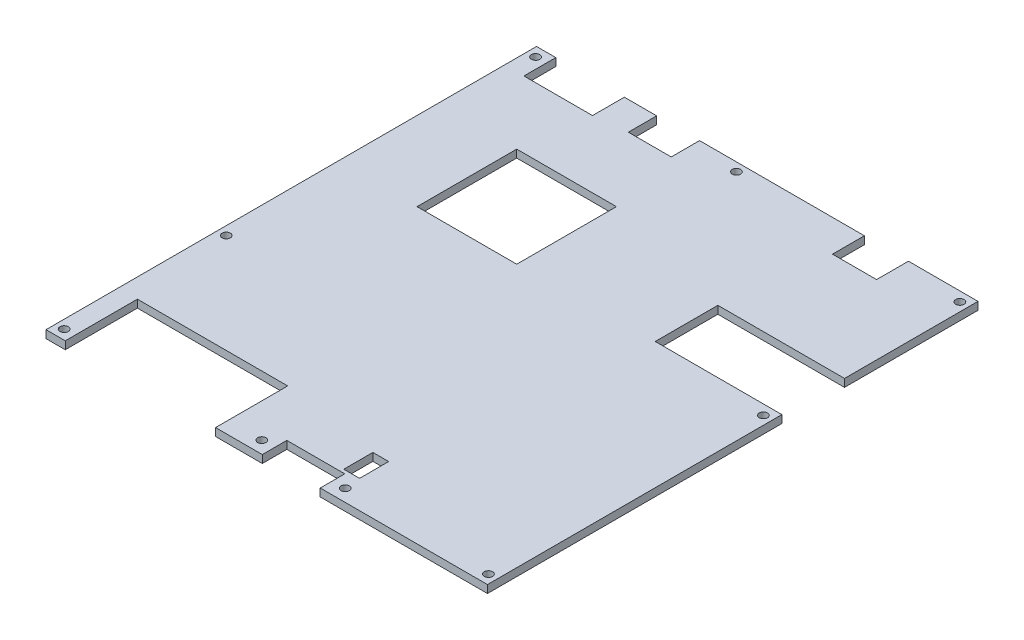
SolidWorks part; units mm, degrees
ref_plane "Front Plane" through (0, 0, 0) normal (0, 0, 1) x (1, 0, 0)
ref_plane "Top Plane" through (0, 0, 0) normal (0, 1, 0) x (1, 0, 0)
ref_plane "Right Plane" through (0, 0, 0) normal (1, 0, 0) x (0, 0, -1)
sketch "Sketch1" plane through (0, 0, 0) normal (0, 1, 0) x (1, 0, 0)
  line L0 (63.5121, 327.7297) -> (677.5121, 327.7297) construction
  line L1 (-90, 100) -> (-82.1461, 100)
  line L2 (-90, 100) -> (-90, -100)
  line L3 (-90, -100) -> (-82.1461, -100)
  line L4 (90, 100) -> (90, 45.5709)
  line L5 (-90, 100) -> (90, -100) construction
  line L6 (-90, -100) -> (90, 100) construction
  line L7 (-6.99, -95) -> (27, -95) construction
  line L8 (-57.7956, 59.7222) -> (-17.1556, 59.7222)
  line L9 (-57.7956, 59.7222) -> (-57.7956, 19.0822)
  line L10 (-57.7956, 19.0822) -> (-17.1556, 19.0822)
  line L11 (-17.1556, 59.7222) -> (-17.1556, 19.0822)
  line L12 (-57.7956, 59.7222) -> (-17.1556, 19.0822) construction
  line L13 (-57.7956, 19.0822) -> (-17.1556, 59.7222) construction
  line L14 (-1.806, -90) -> (21.816, -90)
  line L15 (-1.806, -90) -> (-1.806, -100)
  line L17 (21.816, -90) -> (21.816, -100)
  line L18 (-1.806, -90) -> (21.816, -100) construction
  line L19 (-1.806, -100) -> (21.816, -90) construction
  line L20 (21.816, -100) -> (90, -100)
  line L22 (-82.1461, -100) -> (-82.1461, -70.5895)
  line L23 (-82.1461, -70.5895) -> (-20.8696, -70.5895)
  line L24 (-20.8696, -100) -> (-20.8696, -70.5895)
  line L26 (43.6796, 100) -> (43.6796, 87.0124)
  line L27 (43.6796, 87.0124) -> (61.6362, 87.0124)
  line L28 (61.6362, 100) -> (61.6362, 87.0124)
  line L30 (-41.0187, 100) -> (-41.0187, 88.4478)
  line L31 (-41.0187, 88.4478) -> (-23.5248, 88.4478)
  line L32 (-23.5248, 100) -> (-23.5248, 88.4478)
  line L34 (-82.1461, 100) -> (-82.1461, 87.0124)
  line L35 (-82.1461, 87.0124) -> (-54.1882, 87.0124)
  line L36 (-54.1882, 100) -> (-54.1882, 87.0124)
  line L37 (19.9809, -76.7028) -> (26.4223, -76.7028)
  line L38 (19.9809, -76.7028) -> (19.9809, -88.5675)
  line L39 (19.9809, -88.5675) -> (26.4223, -88.5675)
  line L40 (26.4223, -76.7028) -> (26.4223, -88.5675)
  line L41 (-54.1882, 100) -> (-41.0187, 100)
  line L42 (-23.5248, 100) -> (43.6796, 100)
  line L43 (61.6362, 100) -> (90, 100)
  line L44 (-20.8696, -100) -> (-1.806, -100)
  line L45 (90, 20.0325) -> (90, -100)
  line L46 (90, 45.5709) -> (38.3643, 45.5709)
  line L48 (90, 20.0325) -> (38.3643, 20.0325)
  line L49 (38.3643, 45.5709) -> (38.3643, 20.0325)
  circle A0 centre (-86.5, 96.1111) radius 1.7
  circle A1 centre (-5, 96.5) radius 1.7
  circle A2 centre (86.5, 96.1111) radius 1.7
  circle A3 centre (-86.5, -96.1111) radius 1.7
  circle A4 centre (-6.99, -95) radius 1.7
  circle A5 centre (27, -95) radius 1.7
  circle A6 centre (86.5, -96.1111) radius 1.7
  circle A7 centre (86.5, 16) radius 1.7
  circle A8 centre (-86.5, -30) radius 1.7
  point P0 (0, 0)
  point P26 (-37.4756, 39.4022)
  point P32 (10.005, -95)
  point P34 (10.005, -95)
  dimension "D3" = 3.4
  dimension "D6" = 3.4
  dimension "D9" = 3.4
  dimension "D10" = 3.4
  dimension "D12" = 3.4
  dimension "D15" = 3.4
  dimension "D19" = 3.4
  dimension "D20" = 3.4
  dimension "D23" = 3.4
  dimension "D1" = 180
  dimension "D2" = 200
  dimension "D4" = 3.5
  dimension "D5" = 85
  dimension "D7" = 3.5
  dimension "D8" = 176.5
  dimension "D11" = 3.5
  dimension "D13" = 5
  dimension "D14" = 83.01
  dimension "D16" = 5
  dimension "D17" = 117
  dimension "D18" = 176.5
  dimension "D21" = 116
  dimension "D22" = 3.5
  dimension "D24" = 70
  dimension "D25" = 3.5
  dimension "D26" = 40.64
  dimension "D27" = 40.64
  dimension "D28" = 23.622
  dimension "D29" = 61.2765
  dimension "D30" = 29.4105
  dimension "D31" = 7.8539
  dimension "D32" = 17.9566
  dimension "D33" = 12.9876
  dimension "D34" = 28.3638
  dimension "D35" = 11.5522
  dimension "D36" = 48.9813
  dimension "D37" = 17.4938
  dimension "D38" = 27.958
  dimension "D39" = 12.9876
  dimension "D40" = 7.8539
  dimension "D41" = 11.8646
  dimension "D42" = 6.4414
  dimension "D43" = 11.4325
  dimension "D44" = 63.5777
  dimension "D45" = 32.2044
  dimension "D46" = 40.2778
  dimension "D47" = 25.5384
  dimension "D48" = 51.6357
  dimension "D49" = 54.4291
extrude "Boss-Extrude1" add sketch "Sketch1" along normal blind 3.175
